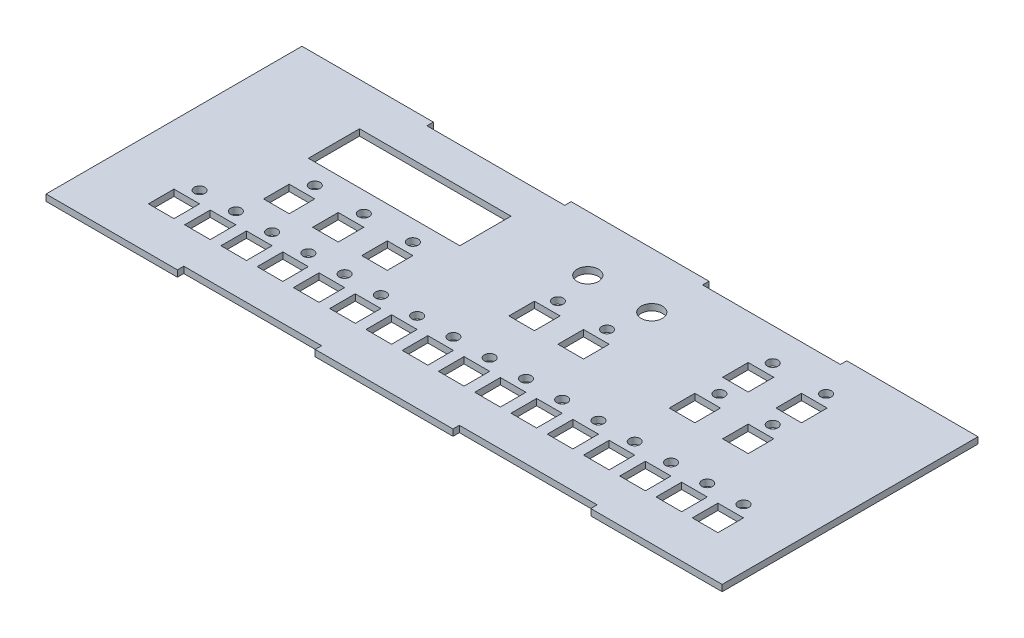
SolidWorks part; units mm, degrees
ref_plane "Front Plane" through (0, 0, 0) normal (0, 0, 1) x (1, 0, 0)
ref_plane "Top Plane" through (0, 0, 0) normal (0, 1, 0) x (1, 0, 0)
ref_plane "Right Plane" through (0, 0, 0) normal (1, 0, 0) x (0, 0, -1)
sketch "Sketch1" plane through (0, 0, 0) normal (0, 1, 0) x (1, 0, 0)
  line L0 (17, 0) -> (17, 12)
  line L1 (0, 0) -> (12, 0)
  line L2 (0, 0) -> (0, 12)
  line L3 (0, 12) -> (12, 12)
  line L4 (12, 0) -> (12, 12)
  line L5 (17, 0) -> (29, 0)
  line L6 (17, 12) -> (29, 12)
  line L7 (29, 0) -> (29, 12)
  line L8 (34, 0) -> (34, 12)
  line L9 (34, 0) -> (46, 0)
  line L10 (34, 12) -> (46, 12)
  line L11 (46, 0) -> (46, 12)
  line L12 (51, 0) -> (51, 12)
  line L13 (51, 0) -> (63, 0)
  line L14 (51, 12) -> (63, 12)
  line L15 (63, 0) -> (63, 12)
  line L16 (68, 0) -> (68, 12)
  line L17 (68, 0) -> (80, 0)
  line L18 (68, 12) -> (80, 12)
  line L19 (80, 0) -> (80, 12)
  line L20 (85, 0) -> (85, 12)
  line L21 (85, 0) -> (97, 0)
  line L22 (85, 12) -> (97, 12)
  line L23 (97, 0) -> (97, 12)
  line L24 (102, 0) -> (102, 12)
  line L25 (102, 0) -> (114, 0)
  line L26 (102, 12) -> (114, 12)
  line L27 (114, 0) -> (114, 12)
  line L28 (119, 0) -> (119, 12)
  line L29 (119, 0) -> (131, 0)
  line L30 (119, 12) -> (131, 12)
  line L31 (131, 0) -> (131, 12)
  line L32 (136, 0) -> (136, 12)
  line L33 (136, 0) -> (148, 0)
  line L34 (136, 12) -> (148, 12)
  line L35 (148, 0) -> (148, 12)
  line L36 (153, 0) -> (153, 12)
  line L37 (153, 0) -> (165, 0)
  line L38 (153, 12) -> (165, 12)
  line L39 (165, 0) -> (165, 12)
  line L40 (170, 0) -> (170, 12)
  line L41 (170, 0) -> (182, 0)
  line L42 (170, 12) -> (182, 12)
  line L43 (182, 0) -> (182, 12)
  line L44 (187, 0) -> (187, 12)
  line L45 (187, 0) -> (199, 0)
  line L46 (187, 12) -> (199, 12)
  line L47 (199, 0) -> (199, 12)
  line L48 (204, 0) -> (204, 12)
  line L49 (204, 0) -> (216, 0)
  line L50 (204, 12) -> (216, 12)
  line L51 (216, 0) -> (216, 12)
  line L52 (221, 0) -> (221, 12)
  line L53 (221, 0) -> (233, 0)
  line L54 (221, 12) -> (233, 12)
  line L55 (233, 0) -> (233, 12)
  line L56 (238, 0) -> (238, 12)
  line L57 (238, 0) -> (250, 0)
  line L58 (238, 12) -> (250, 12)
  line L59 (250, 0) -> (250, 12)
  line L60 (255, 0) -> (255, 12)
  line L61 (255, 0) -> (267, 0)
  line L62 (255, 12) -> (267, 12)
  line L63 (267, 0) -> (267, 12)
  line L65 (230, 51.2) -> (242, 51.2)
  line L66 (205, 39.2) -> (217, 39.2)
  line L67 (205, 39.2) -> (205, 51.2)
  line L68 (205, 51.2) -> (217, 51.2)
  line L69 (217, 39.2) -> (217, 51.2)
  line L70 (230, 39.2) -> (230, 51.2)
  line L71 (230, 39.2) -> (242, 39.2)
  line L72 (242, 39.2) -> (242, 51.2)
  line L73 (230, 76.2) -> (242, 76.2)
  line L74 (230, 64.2) -> (230, 76.2)
  line L75 (230, 64.2) -> (242, 64.2)
  line L76 (242, 64.2) -> (242, 76.2)
  line L77 (205, 76.2) -> (217, 76.2)
  line L78 (205, 64.2) -> (205, 76.2)
  line L79 (205, 64.2) -> (217, 64.2)
  line L80 (217, 64.2) -> (217, 76.2)
  line L81 (205, 51.2) -> (230, 51.2) construction
  line L82 (48, 29) -> (48, 41)
  line L83 (19, 80) -> (90, 80)
  line L84 (19, 80) -> (19, 56)
  line L85 (19, 56) -> (90, 56)
  line L86 (90, 80) -> (90, 56)
  line L87 (25, 29) -> (37, 29)
  line L88 (25, 29) -> (25, 41)
  line L89 (25, 41) -> (37, 41)
  line L90 (37, 29) -> (37, 41)
  line L91 (48, 41) -> (60, 41)
  line L92 (60, 29) -> (60, 41)
  line L93 (48, 29) -> (60, 29)
  line L94 (71, 29) -> (71, 41)
  line L95 (71, 41) -> (83, 41)
  line L96 (83, 29) -> (83, 41)
  line L97 (71, 29) -> (83, 29)
  line L98 (25, 29) -> (48, 29) construction
  line L99 (153, 51) -> (165, 51)
  line L100 (130, 39) -> (142, 39)
  line L101 (130, 39) -> (130, 51)
  line L102 (130, 51) -> (142, 51)
  line L103 (142, 39) -> (142, 51)
  line L104 (153, 39) -> (153, 51)
  line L105 (153, 39) -> (165, 39)
  line L106 (165, 39) -> (165, 51)
  line L107 (132, 74) -> (162, 74) construction
  line L108 (6.5, 17.5) -> (23.5, 17.5) construction
  line L109 (211, 56.7) -> (236, 56.7) construction
  line L110 (31.5, 46.5) -> (54.5, 46.5) construction
  line L111 (135.5, 56.5) -> (158.5, 56.5) construction
  line L112 (33.6, -20) -> (33.6, -17)
  line L113 (98.2, -20) -> (162.8, -20)
  line L114 (-28, -20) -> (-28, 100)
  line L115 (-28, 100) -> (33.6, 100)
  line L116 (289, -20) -> (289, 100)
  line L117 (33.6, -17) -> (98.2, -17)
  line L118 (98.2, -17) -> (98.2, -20)
  line L119 (33.6, -20) -> (-28, -20)
  line L120 (162.8, -20) -> (162.8, -17)
  line L121 (162.8, -17) -> (227.4, -17)
  line L122 (227.4, -17) -> (227.4, -20)
  line L123 (227.4, -20) -> (289, -20)
  line L124 (33.6, 100) -> (33.6, 97)
  line L125 (33.6, 97) -> (98.2, 97)
  line L126 (98.2, 97) -> (98.2, 100)
  line L127 (98.2, 100) -> (162.8171, 100)
  line L128 (162.8171, 100) -> (162.8171, 97)
  line L129 (162.8171, 97) -> (227.4171, 97)
  line L130 (227.4171, 97) -> (227.4171, 100)
  line L131 (289.0171, 99.9361) -> (227.4171, 100)
  line L132 (289, 100) -> (289.0171, 99.9361)
  circle A0 centre (132, 74) radius 5
  circle A1 centre (162, 74) radius 5
  circle A2 centre (6.5, 17.5) radius 2.5
  circle A3 centre (23.5, 17.5) radius 2.5
  circle A4 centre (40.5, 17.5) radius 2.5
  circle A5 centre (57.5, 17.5) radius 2.5
  circle A6 centre (74.5, 17.5) radius 2.5
  circle A7 centre (91.5, 17.5) radius 2.5
  circle A8 centre (108.5, 17.5) radius 2.5
  circle A9 centre (125.5, 17.5) radius 2.5
  circle A10 centre (142.5, 17.5) radius 2.5
  circle A11 centre (159.5, 17.5) radius 2.5
  circle A12 centre (176.5, 17.5) radius 2.5
  circle A13 centre (193.5, 17.5) radius 2.5
  circle A14 centre (210.5, 17.5) radius 2.5
  circle A15 centre (227.5, 17.5) radius 2.5
  circle A16 centre (244.5, 17.5) radius 2.5
  circle A17 centre (261.5, 17.5) radius 2.5
  circle A18 centre (211, 56.7) radius 2.5
  circle A19 centre (236, 56.7) radius 2.5
  circle A20 centre (236, 81.7) radius 2.5
  circle A21 centre (211, 81.7) radius 2.5
  circle A22 centre (31.5, 46.5) radius 2.5
  circle A23 centre (54.5, 46.5) radius 2.5
  circle A24 centre (77.5, 46.5) radius 2.5
  circle A25 centre (135.5, 56.5) radius 2.5
  circle A26 centre (158.5, 56.5) radius 2.5
  dimension "D20" = 10
  dimension "D23" = 20
  dimension "D28" = 5
  dimension "D34" = 5
  dimension "D39" = 5
  dimension "D45" = 5
  dimension "D5" = 12
  dimension "D6" = 12
  dimension "D9" = 25
  dimension "D10" = 71
  dimension "D11" = 24
  dimension "D12" = 12
  dimension "D13" = 12
  dimension "D15" = 28
  dimension "D16" = 12
  dimension "D17" = 12
  dimension "D19" = 23
  dimension "D22" = 30
  dimension "D24" = 16
  dimension "D25" = 12
  dimension "D27" = 17
  dimension "D31" = 25
  dimension "D32" = 5.5
  dimension "D33" = 6
  dimension "D36" = 23
  dimension "D37" = 5.5
  dimension "D38" = 6.5
  dimension "D41" = 23
  dimension "D42" = 5.5
  dimension "D43" = 5.5
  dimension "D44" = 12
  dimension "D46" = 13
  dimension "D47" = 15
  dimension "D48" = 40
  dimension "D49" = 3
  dimension "D50" = 6
  dimension "D51" = 5.5
  dimension "D52" = 61.6
  dimension "D53" = 64.6
  dimension "D54" = 40
  dimension "D55" = 47
  dimension "D56" = 2
  dimension "D57" = 23
  dimension "D58" = 120
  dimension "D59" = 317
  dimension "D60" = 3
  dimension "D61" = 61.6
  dimension "D62" = 64.6
  dimension "D63" = 61.6
  dimension "D64" = 64.6
  dimension "D65" = 61.6
  dimension "D66" = 64.6
  dimension "D14" = 3
  dimension "D18" = 2
  dimension "D21" = 2
  dimension "D26" = 16
  dimension "D7" = 2
  dimension "D8" = 2
  dimension "D29" = 2
  dimension "D30" = 2
  dimension "D35" = 3
  dimension "D40" = 2
extrude "Boss-Extrude1" add sketch "Sketch1" along normal blind 3 contours L116 L131 L130 L129 L128 L127 L126 L125 L124 L115 L114 L119 L112 L117 L118 L113 L120 L121 L122 L123 A26 A25 A24 A23 A22 A21 A20 A19 A18 A17 A16 A15 A14 A13 A12
